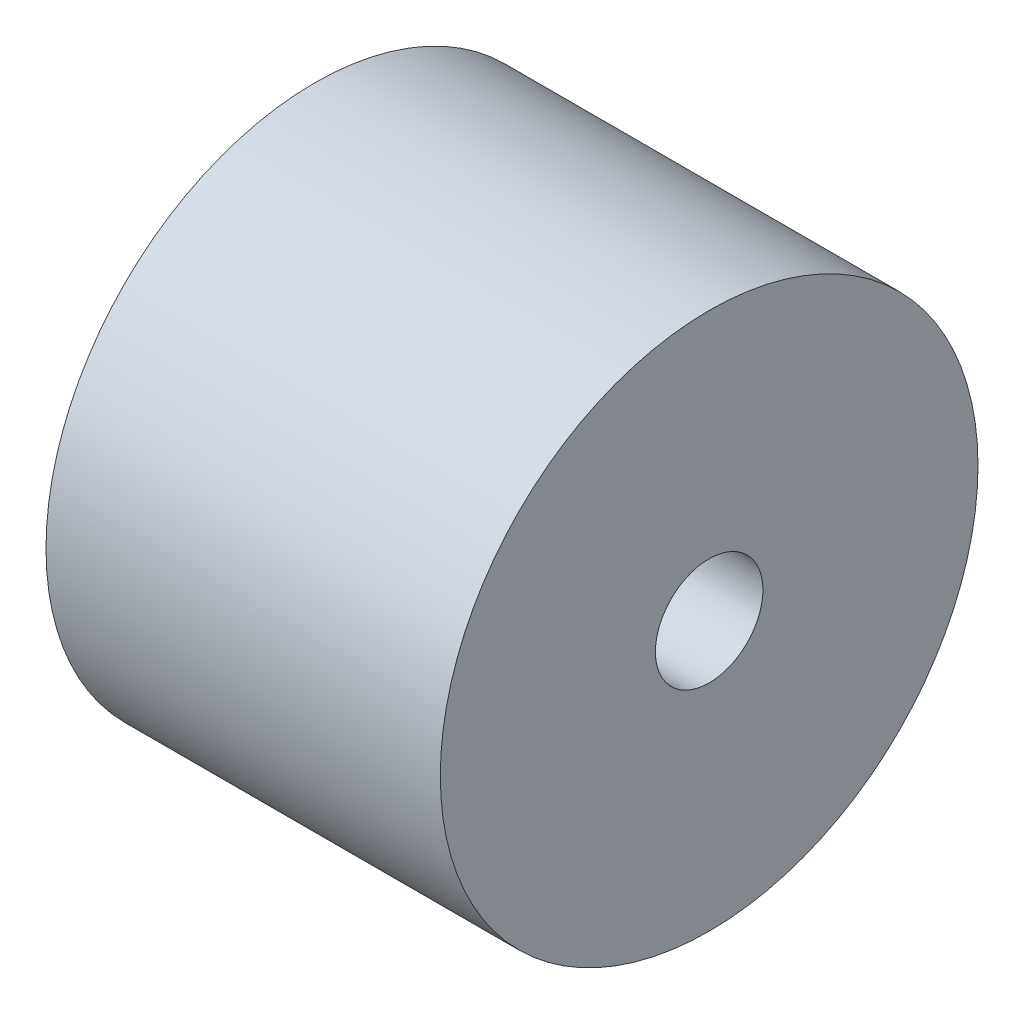
SolidWorks part; units mm, degrees
ref_plane "Front Plane" through (0, 0, 0) normal (0, 0, 1) x (1, 0, 0)
ref_plane "Top Plane" through (0, 0, 0) normal (0, 1, 0) x (1, 0, 0)
ref_plane "Right Plane" through (0, 0, 0) normal (1, 0, 0) x (0, 0, -1)
sketch "Skizze1" plane through (0, 0, 0) normal (0, 1, 0) x (1, 0, 0)
  line L0 (0, 0) -> (0, 15)
  line L1 (0, 15) -> (22, 15)
  line L2 (22, 15) -> (22, 0)
  line L3 (22, 0) -> (0, 0)
  line L4 (-5.3722, 0) -> (26.2911, 0) construction
revolve "Rotation1" add sketch "Skizze1" angle 360 about L4
sketch "Skizze2" plane through (0, 0, 0) normal (-1, 0, 0) x (0, 0, 1)
  circle A0 centre (0, 0) radius 3
extrude "Schnitt-Linear austragen1" cut sketch "Skizze2" against normal through all both and the other way through all
